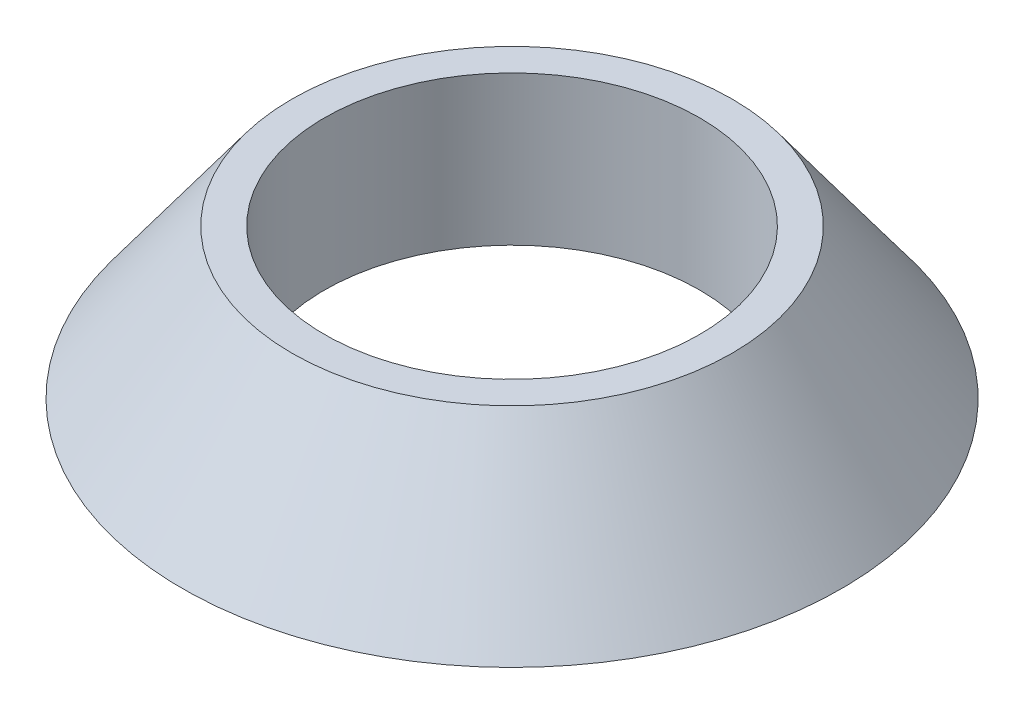
SolidWorks part; units mm, degrees
ref_plane "Front Plane" through (0, 0, 0) normal (0, 0, 1) x (1, 0, 0)
ref_plane "Top Plane" through (0, 0, 0) normal (0, 1, 0) x (1, 0, 0)
ref_plane "Right Plane" through (0, 0, 0) normal (1, 0, 0) x (0, 0, -1)
sketch "Esquisse1" plane through (0, 0, 0) normal (0, 0, 1) x (1, 0, 0)
  line L0 (0, 0) -> (20.7687, 0) construction
  line L1 (20.7687, 0) -> (20.7687, 16.5109)
  line L2 (20.7687, 16.5109) -> (24.3642, 16.5109)
  line L3 (24.3642, 16.5109) -> (36.4753, 0)
  line L4 (36.4753, 0) -> (20.7687, 0)
  line L5 (0, 0) -> (0, 50000) construction
revolve "Révolution1" add sketch "Esquisse1" angle 360 about L5
